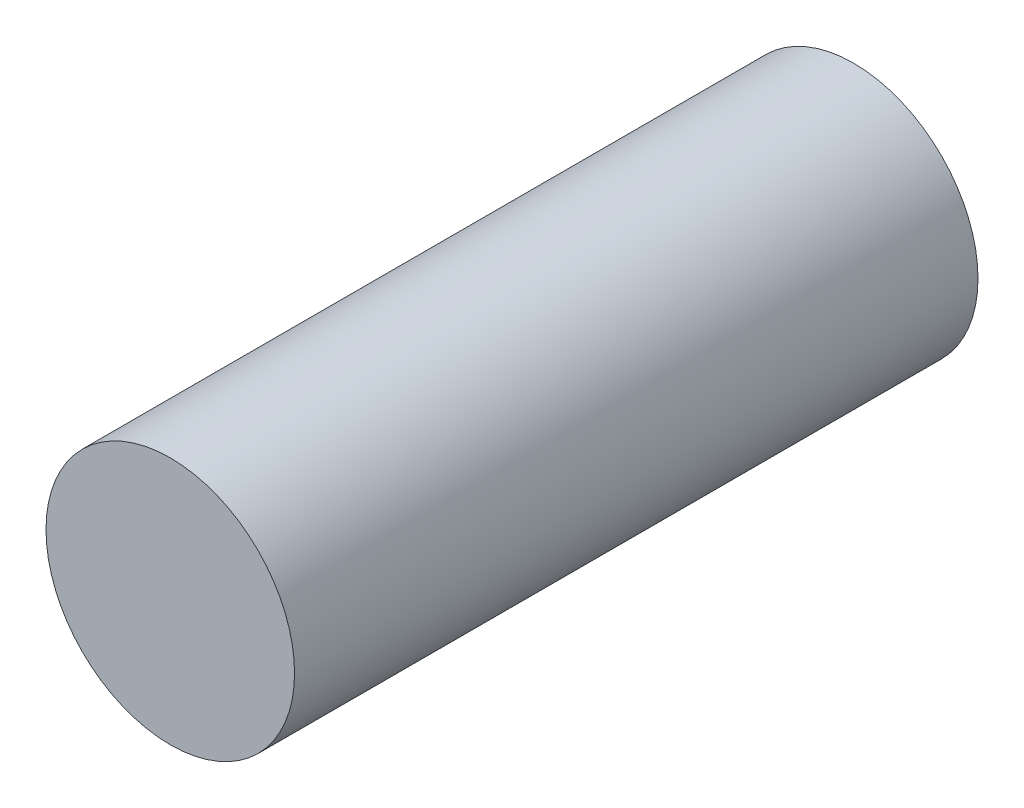
SolidWorks part; units mm, degrees
ref_plane "Front Plane" through (0, 0, 0) normal (0, 0, 1) x (1, 0, 0)
ref_plane "Top Plane" through (0, 0, 0) normal (0, 1, 0) x (1, 0, 0)
ref_plane "Right Plane" through (0, 0, 0) normal (1, 0, 0) x (0, 0, -1)
sketch "Sketch1" plane through (0, 0, 0) normal (0, 0, 1) x (1, 0, 0)
  circle A0 centre (0, 0) radius 10
  dimension "D1" = 20
extrude "Boss-Extrude1" add sketch "Sketch1" along normal blind 55
